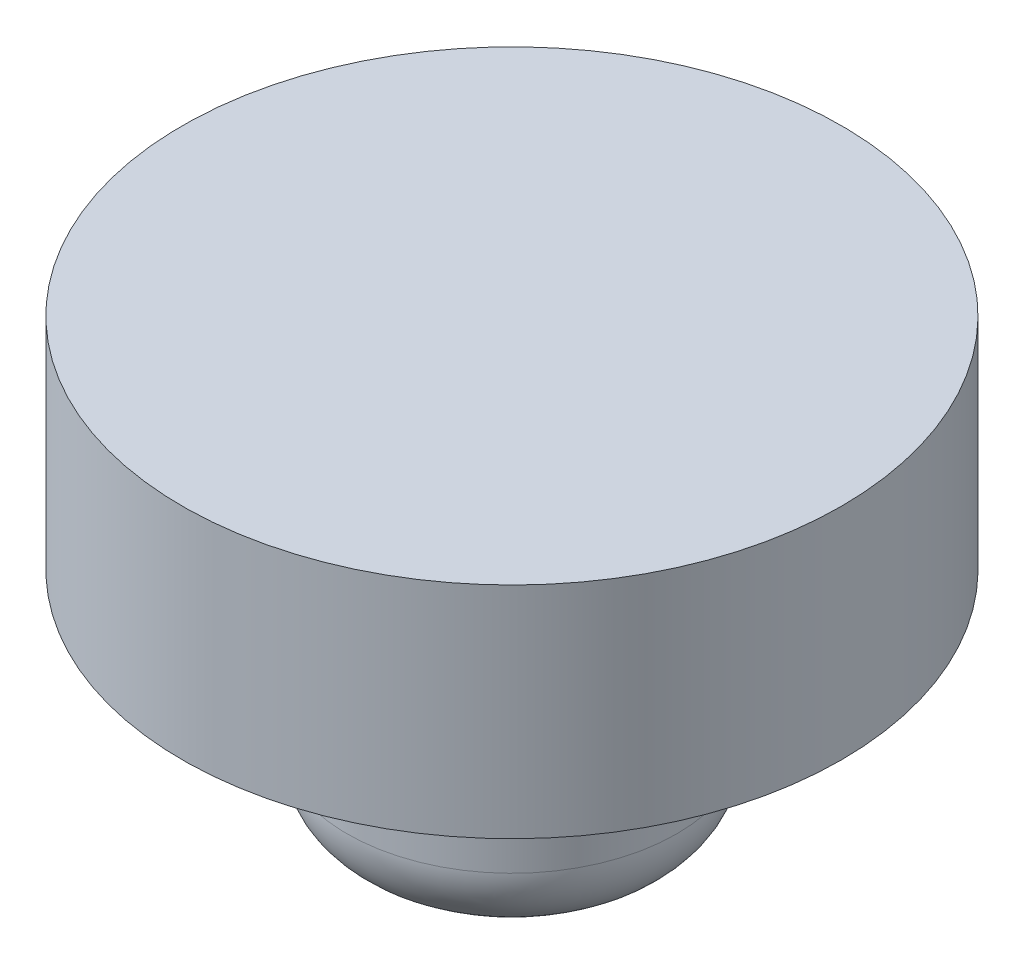
SolidWorks part; units mm, degrees
ref_plane "Front Plane" through (0, 0, 0) normal (0, 0, 1) x (1, 0, 0)
ref_plane "Top Plane" through (0, 0, 0) normal (0, 1, 0) x (1, 0, 0)
ref_plane "Right Plane" through (0, 0, 0) normal (1, 0, 0) x (0, 0, -1)
sketch "Sketch1" plane through (0, -270, 0) normal (0, -1, 0) x (1, 0, 0)
  line L0 (0, 914.6526) -> (0, 1112.3525) construction
  line L1 (-216.4624, 914.6526) -> (216.4624, 914.6526) construction
  line L2 (-70, 999.1895) -> (262.0639, 999.1895) construction
  circle A0 centre (70, 999.1895) radius 45
  circle A1 centre (70, 999.1895) radius 22.5
  dimension "D1" = 70
  dimension "D2" = 90
  dimension "D3" = 45
extrude "Boss-Extrude1" add sketch "Sketch1" along normal blind 30
sketch "Sketch2" plane through (0, -270, 0) normal (0, -1, 0) x (1, 0, 0)
  circle A0 centre (70, 999.1895) radius 22.5
extrude "Boss-Extrude2" add sketch "Sketch2" along normal blind 60
fillet "Fillet1" radius 10 1 edges at (92.5, -330, 999.1895)
